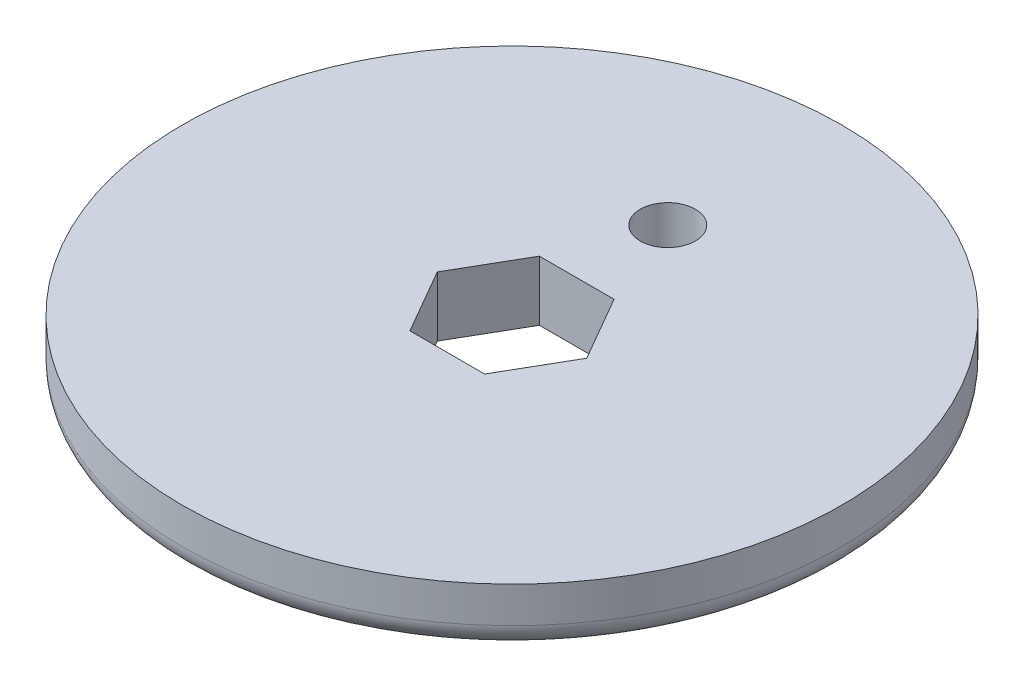
SolidWorks part; units mm, degrees
ref_plane "Front Plane" through (0, 0, 0) normal (0, 0, 1) x (1, 0, 0)
ref_plane "Top Plane" through (0, 0, 0) normal (0, 1, 0) x (1, 0, 0)
ref_plane "Right Plane" through (0, 0, 0) normal (1, 0, 0) x (0, 0, -1)
sketch "Sketch1" plane through (0, 0, 0) normal (0, 1, 0) x (1, 0, 0)
  line L1 (7.9189, 0) -> (3.9595, 6.858)
  line L2 (3.9595, 6.858) -> (-3.9595, 6.858)
  line L3 (-3.9595, 6.858) -> (-7.9189, 0)
  line L4 (-7.9189, 0) -> (-3.9595, -6.858)
  line L5 (-3.9595, -6.858) -> (3.9595, -6.858)
  line L6 (3.9595, -6.858) -> (7.9189, 0)
  circle A0 centre (0, 0) radius 6.858 construction
  circle A1 centre (0, 0) radius 34.925
  dimension "D2" = 69.85
  dimension "D1" = 13.716
extrude "Boss-Extrude1" add sketch "Sketch1" along normal blind 6.35
fillet "Fillet1" radius 2.54 1 edges at (0, 0, 34.925)
sketch "Sketch2" plane through (0, 6.35, 0) normal (0, 1, 0) x (1, 0, 0)
  circle A0 centre (0, 16.51) radius 2.921
  dimension "D2" = 5.842
  dimension "D1" = 16.51
extrude "Cut-Extrude1" cut sketch "Sketch2" against normal through all
